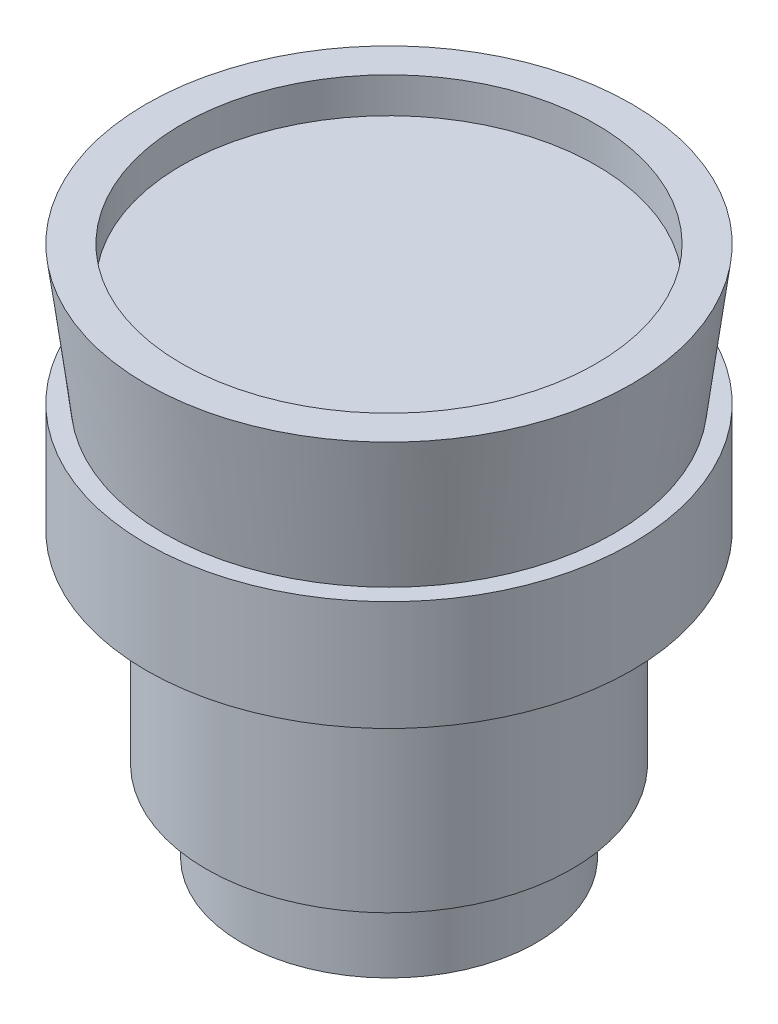
SolidWorks part; units mm, degrees
ref_plane "Front Plane" through (0, 0, 0) normal (0, 0, 1) x (1, 0, 0)
ref_plane "Top Plane" through (0, 0, 0) normal (0, 1, 0) x (1, 0, 0)
ref_plane "Right Plane" through (0, 0, 0) normal (1, 0, 0) x (0, 0, -1)
sketch "Sketch1" plane through (0, 0, 0) normal (1, 0, 0) x (0, 0, -1)
  line L0 (0, 71.6296) -> (0, -39.8706) construction
  line L1 (-49.0321, 0) -> (45.1423, 0) construction
  line L2 (0, 17.78) -> (-17.399, 17.78)
  line L4 (-17.399, 7.874) -> (-17.399, 0)
  line L5 (-17.399, 0) -> (-13.1064, 0)
  line L6 (-13.1064, 0) -> (-13.1064, -14.478)
  line L7 (-13.1064, -14.478) -> (-10.5664, -14.478)
  line L8 (-10.5664, -14.478) -> (-10.5664, -20.32)
  line L9 (-10.5664, -20.32) -> (0, -20.32)
  line L10 (0, 17.78) -> (0, -20.32)
  line L11 (-17.399, 17.78) -> (-16.129, 7.874)
  line L12 (-16.129, 7.874) -> (-17.399, 7.874)
  point P7 (-15.2527, 0)
  dimension "D1" = 17.399
  dimension "D2" = 17.78
  dimension "D3" = 7.874
  dimension "D4" = 14.478
  dimension "D5" = 5.842
  dimension "D6" = 13.1064
  dimension "D7" = 17.399
  dimension "D8" = 2.54
  dimension "D9" = 1.27
revolve "Revolve1" add sketch "Sketch1" angle 360 about L10
cosmetic thread "Cosmetic Thread1" parameters "D1"=2.4999, "D2"=23.8481
sketch "Sketch2" plane through (0, 17.78, 0) normal (0, 1, 0) x (1, 0, 0)
  circle A0 centre (0, 0) radius 14.859
  circle A1 centre (0, 0) radius 17.399 construction
  dimension "D1" = 2.54
extrude "Cut-Extrude1" cut sketch "Sketch2" against normal blind 2.54
